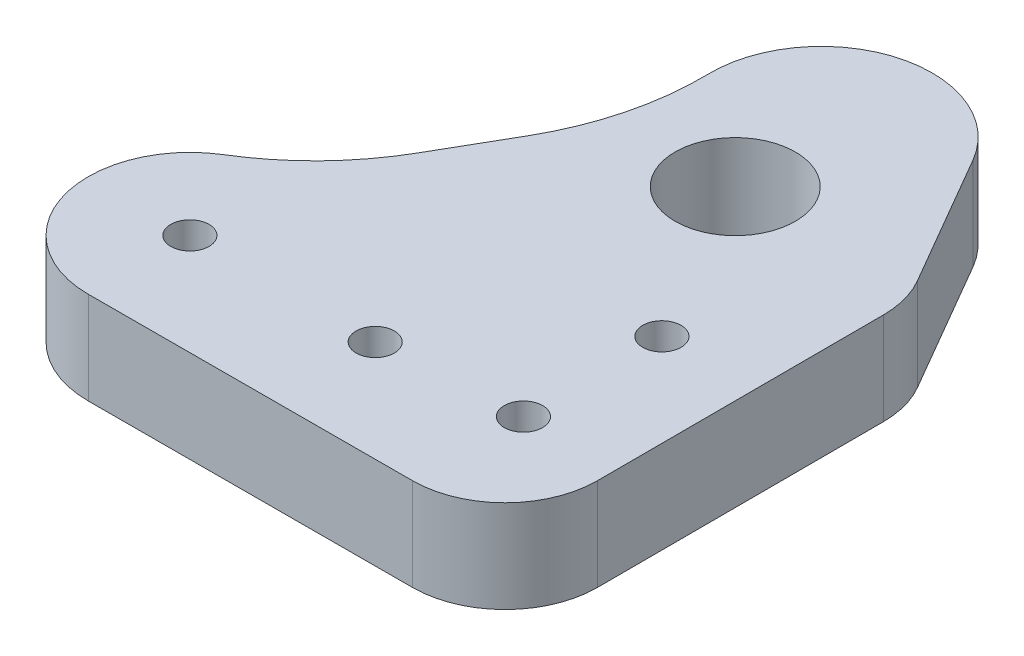
SolidWorks part; units mm, degrees
ref_plane "Front Plane" through (0, 0, 0) normal (0, 0, 1) x (1, 0, 0)
ref_plane "Top Plane" through (0, 0, 0) normal (0, 1, 0) x (1, 0, 0)
ref_plane "Right Plane" through (0, 0, 0) normal (1, 0, 0) x (0, 0, -1)
sketch "Sketch1" plane through (0, 0, 0) normal (0, 1, 0) x (1, 0, 0)
  line L0 (23.7035, -15.1524) -> (23.6421, 15.8283)
  line L1 (22.2924, 20.8256) -> (13.9961, 35.1297)
  line L2 (-12.3659, 13.3424) -> (-16.7235, 5.7601)
  line L3 (-21.2766, -25.2416) -> (13.7234, -25.1722)
  circle A0 centre (-21.2984, -14.2417) radius 2.07
  arc A1 (23.6421, 15.8283) -> (22.2924, 20.8256) centre (13.6421, 15.8085) ccw
  arc A2 (13.9961, 35.1297) -> (-8.382, 28.8753) centre (3.6157, 29.1091) ccw
  arc A3 (-12.3659, 13.3424) -> (-8.382, 28.8753) centre (-38.3764, 28.2908) ccw
  arc A4 (-27.0494, -4.8648) -> (-16.7235, 5.7601) centre (-42.734, 20.7085) ccw
  arc A5 (-27.0494, -4.8648) -> (-21.2766, -25.2416) centre (-21.2984, -14.2417) ccw
  arc A6 (13.7234, -25.1722) -> (23.7035, -15.1524) centre (13.7035, -15.1722) ccw
  circle A7 centre (-1.2984, -14.202) radius 2.07
  circle A8 centre (13.6996, -13.1722) radius 2.07
  circle A9 centre (13.6698, 1.8277) radius 2.07
  circle A10 centre (3.6157, 19.8078) radius 6.5
  dimension "D1" = 4.14
  dimension "D2" = 13
  dimension "D3" = 10
  dimension "D4" = 12
  dimension "D5" = 30
  dimension "D6" = 11
  dimension "D7" = 3.6157
  dimension "D8" = 13.6421
  dimension "D9" = 13.6698
  dimension "D10" = 13.6996
  dimension "D11" = 13.7035
  dimension "D12" = 13.7234
  dimension "D13" = 13.9961
  dimension "D14" = 8.382
  dimension "D15" = 12.3659
  dimension "D16" = 16.7235
  dimension "D17" = 1.2984
  dimension "D18" = 1.8277
  dimension "D19" = 5.7601
  dimension "D20" = 45
  dimension "D30" = 13.1722
  dimension "D31" = 14.202
extrude "Boss-Extrude1" add sketch "Sketch1" along normal blind 10
